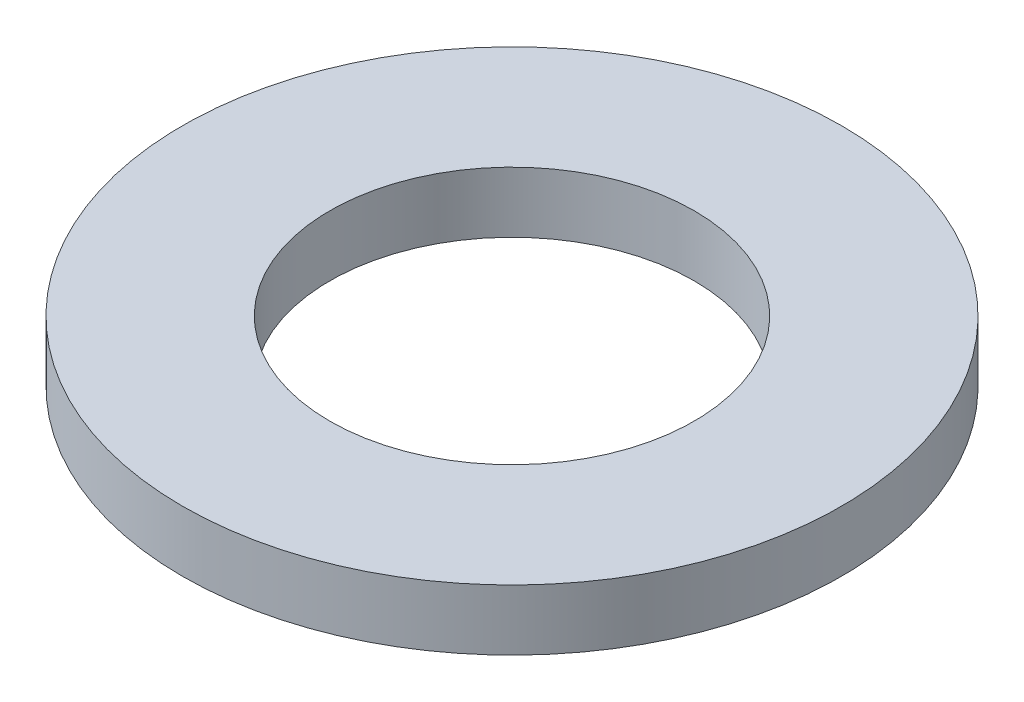
SolidWorks part; units mm, degrees
ref_plane "Front Plane" through (0, 0, 0) normal (0, 0, 1) x (1, 0, 0)
ref_plane "Top Plane" through (0, 0, 0) normal (0, 1, 0) x (1, 0, 0)
ref_plane "Right Plane" through (0, 0, 0) normal (1, 0, 0) x (0, 0, -1)
sketch "Sketch1" plane through (0, 0, 0) normal (0, 1, 0) x (1, 0, 0)
  circle A0 centre (-13.4903, 17.5468) radius 1.524
  circle A1 centre (-13.4903, 17.5468) radius 2.7559
  dimension "D1" = 5.5118
  dimension "D2" = 3.048
extrude "Boss-Extrude1" add sketch "Sketch1" along normal blind 0.508
